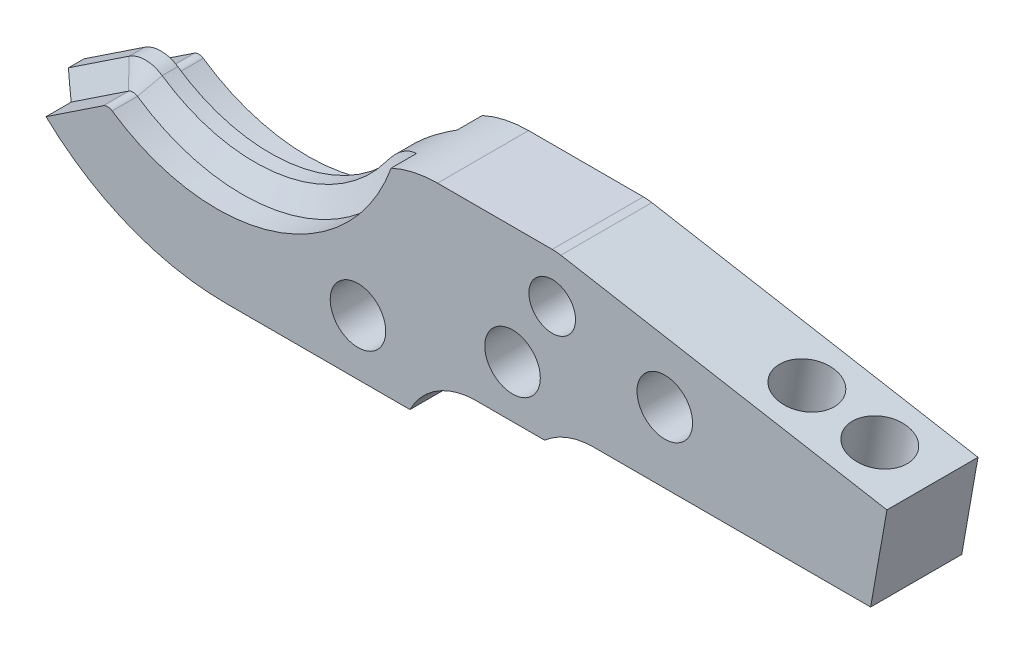
SolidWorks part; units mm, degrees
material "4140/42 H.R STEEL"
ref_plane "Front Plane" through (0, 0, 0) normal (0, 0, 1) x (1, 0, 0)
ref_plane "Top Plane" through (0, 0, 0) normal (0, 1, 0) x (1, 0, 0)
ref_plane "Right Plane" through (0, 0, 0) normal (1, 0, 0) x (0, 0, -1)
sketch "Sketch1" plane through (0, 0, 0) normal (0, 0, 1) x (1, 0, 0)
  line L0 (-18.5234, -21.0526) -> (-31.9565, -29.9967)
  line L1 (26.5581, -9) -> (139.7, -9)
  line L2 (139.7, -9) -> (139.7, -21.7)
  line L3 (139.7, -21.7) -> (152.4, -21.7)
  line L4 (152.4, -21.7) -> (152.4, -38)
  line L5 (33.101, -45) -> (1.5875, -45)
  line L6 (0, 0) -> (-18.5234, -21.0526) construction
  line L9 (152.4, -38) -> (44.45, -38)
  arc A0 (-18.5234, -21.0526) -> (26.5581, -9) centre (0, 0) ccw
  arc A1 (-31.9565, -29.9967) -> (1.5875, -45) centre (1.5875, 0) ccw
  circle A2 centre (-18.7477, -27.305) radius 5.08 construction
  arc A3 (44.45, -38) -> (33.101, -45) centre (44.45, -50.7) ccw
  dimension "D1" = 28.0416
  dimension "D7" = 45
  dimension "D2" = 10.16
  dimension "D12" = 25.4
  dimension "D3" = 1.5875
  dimension "D4" = 152.4
  dimension "D5" = 12.7
  dimension "D6" = 22.225
  dimension "D8" = 9
  dimension "D9" = 12.7
  dimension "D10" = 7
  dimension "D11" = 107.95
  dimension "D13" = 165
extrude "Extrude1" add sketch "Sketch1" along normal blind 15.621
ref_plane "Plane1" through (26.5581, -9, 15.621) normal (-0.321, -0.9471, 0) x (0.9471, -0.321, 0)
sketch "Sketch3" plane through (26.5581, -9, 15.621) normal (-0.321, -0.9471, 0) x (0.9471, -0.321, 0)
  line L0 (-25.4, 0) -> (3.7084, 0)
  line L1 (3.7084, 0) -> (3.7084, -4.336)
  line L2 (3.7084, -4.336) -> (0, -6.477)
  line L3 (0, -6.477) -> (0, -9.144)
  line L4 (0, -9.144) -> (3.7084, -11.285)
  line L5 (3.7084, -11.285) -> (3.7084, -15.621)
  line L6 (3.7084, -15.621) -> (-25.4, -15.621)
  line L7 (-25.4, -15.621) -> (-25.4, -7.8105)
  line L8 (-25.4, -7.8105) -> (-25.4, 0)
  line L9 (0, 0) -> (0, -15.621) construction
  line L10 (0, -7.8105) -> (-25.4, -7.8105) construction
  line L11 (107.1562, 0) -> (0, 0) construction
  line L12 (107.1562, -15.621) -> (0, -15.621) construction
  dimension "D2" = 2.667
  dimension "D1" = 60
  dimension "D4" = 30
  dimension "D6" = 3.7084
  dimension "D7" = 25.4
sketch "Sketch4" plane through (0, 0, 15.621) normal (0, 0, 1) x (1, 0, 0)
  line L0 (-18.5234, -21.0526) -> (-31.9565, -29.9967) construction
  line L1 (-21.5631, -23.0765) -> (-26.708, -26.5021)
  line L2 (-18.5234, -21.0526) -> (-31.9565, -29.9967) construction
  line L3 (-26.708, -26.5021) -> (-31.9565, -29.9967)
  arc A0 (-18.5234, -21.0526) -> (26.5581, -9) centre (0, 0) ccw construction
  arc A1 (-15.8723, -23.1171) -> (26.5581, -9) centre (0, 0) ccw
  circle A2 centre (-18.7477, -27.305) radius 5.08 construction
  arc A3 (-15.8723, -23.1171) -> (-21.5631, -23.0765) centre (-18.7477, -27.305) ccw
  circle A4 centre (-23.8926, -30.7306) radius 5.08 construction
  arc A5 (-31.9565, -29.9967) -> (1.5875, -45) centre (1.5875, 0) ccw construction
  dimension "D1" = 10.16
sweep "Cut-Sweep1" cut profiles "Sketch3" path "Sketch4"
sketch "Sketch5" plane through (0, 0, 15.621) normal (0, 0, 1) x (1, 0, 0)
  line L0 (38.333, 16.8038) -> (31.5322, 12.2756)
  line L1 (37.8261, -9) -> (139.7, -9)
  line L4 (1.5875, -45) -> (152.4, -45)
  line L5 (152.4, -45) -> (152.4, -21.7)
  line L6 (152.4, -21.7) -> (139.7, -21.7)
  line L7 (139.7, -21.7) -> (139.7, -9)
  line L8 (-31.9565, -29.9967) -> (-21.7058, -23.1715) construction
  line L9 (-83.2798, -105.3294) -> (187.5268, -105.3294)
  line L10 (-83.2798, -105.3294) -> (-83.2798, 60.7736)
  line L11 (-83.2798, 60.7736) -> (187.5268, 60.7736)
  line L12 (187.5268, -105.3294) -> (187.5268, 60.7736)
  arc A1 (-29.3263, -32.7007) -> (1.5875, -45) centre (1.5875, 0) ccw construction
  arc A2 (39.8354, 23.7087) -> (1.5875, -45) centre (1.5875, 0) ccw
  arc A3 (31.5322, 12.2756) -> (24.3124, 13.9728) centre (28.7168, 16.5041) cw
  arc A4 (22.5243, -16.7029) -> (37.8261, -9) centre (37.8261, -28.05) cw
  arc A5 (39.8354, 23.7087) -> (38.333, 16.8038) centre (35.5176, 21.0322) cw
  arc A8 (22.5243, -16.7029) -> (24.3124, 13.9728) centre (0, 0) cw
  spline S3 degree 3 poles (30.0703, -10.1902) (22.7075, -31.9169) (0.9404, -39.1591) (-17.9714, -26.1743) knots 0 0 0 0 1 1 1 1 weights 1 0.735689 0.735689 1 construction
  spline S4 degree 3 poles (30.0703, -10.1902) (22.7075, -31.9169) (0.9404, -39.1591) (-17.9714, -26.1743) knots 0 0 0 0 1 1 1 1 weights 1 0.735689 0.735689 1 construction
  dimension "D1" = 5.08
  dimension "D2" = 19.05
  dimension "D3" = 28.0416
extrude "Extrude2" cut sketch "Sketch5" against normal through all
sketch "Sketch6" plane through (0, 0, 0) normal (0, 0, -1) x (-1, 0, 0)
  circle A0 centre (-57.5, -17.4625) radius 4
  dimension "D1" = 8
  dimension "D2" = 57.5
  dimension "D3" = 17.4625
extrude "Extrude3" cut sketch "Sketch6" against normal through all
sketch "Sketch7" plane through (0, 0, 0) normal (0, 0, -1) x (-1, 0, 0)
  line L0 (-139.7, -9) -> (-37.8261, -9) construction
  line L1 (-58.9695, -9.1286) -> (-114.9066, -18.9918)
  line L2 (-1.5875, -45) -> (-33.101, -45) construction
  line L3 (-57.5, -9) -> (-152.4, -9)
  line L4 (-152.4, -9) -> (-152.4, -45)
  line L5 (-152.4, -45) -> (-110.3206, -45)
  line L6 (-114.9066, -18.9918) -> (-110.3206, -45)
  line L7 (-114.3, -17.4625) -> (-114.3, -85.3181) construction
  line L8 (-105.5306, -72.1653) -> (-122.6103, 24.6983) construction
  line L9 (-152.4, -38) -> (-152.4, -21.7) construction
  arc A0 (-57.5, -9) -> (-58.9695, -9.1286) centre (-57.5, -17.4625) ccw
  circle A3 centre (-57.5, -17.4625) radius 56.8 construction
  dimension "D1" = 10
  dimension "D3" = 114.3
  dimension "D4" = 10
extrude "Extrude4" cut sketch "Sketch7" against normal through all
sketch "Sketch8" plane through (0.9701, 1.0983, 0) normal (0.1736, 0.9848, 0) x (0.9848, -0.1736, 0)
  line L0 (62.8941, 0) -> (54.8941, 0) construction
  line L1 (62.8941, 0) -> (54.8941, 0) construction
  line L2 (58.8941, 0) -> (58.8941, -15.621) construction
  line L3 (58.8941, -7.8105) -> (106.5191, -7.8105) construction
  line L4 (58.8941, -15.621) -> (115.6941, -15.621) construction
  circle A0 centre (106.5191, -7.8105) radius 4.7625
  circle A1 centre (93.8191, -7.8105) radius 4.7625
  dimension "D1" = 9.525
  dimension "D2" = 47.625
  dimension "D3" = 12.7
extrude "Extrude5" [suppressed] cut sketch "Sketch8" against normal blind 16.8402
hole_wizard "3/8 (0.375) Diameter Hole1" positions "Sketch10" profile "Sketch9" hole size "3/8" standard "Peddi Ansi Inch"
sketch "Sketch10" plane through (0, 0, 0) normal (0, 0, -1) x (-1, 0, 0)
  line L0 (-1.5875, -45) -> (-33.101, -45) construction
  line L2 (-1.5875, -45) -> (-33.101, -45) construction
  point P0 (-24.1816, -35.475)
  point P1 (-50.6941, -29.125)
  point P3 (-76.8066, -22.775)
  dimension "D1" = 90.725
  dimension "D2" = 64.2125
  dimension "D3" = 38.1
  dimension "D4" = 9.525
  dimension "D5" = 22.225
  dimension "D6" = 15.875
sketch "Sketch9" plane through (24.1816, -35.475, 0) normal (1, 0, 0) x (0, 1, 0)
  line L0 (0, 0) -> (0, 27.1334)
  line L1 (0, 27.1334) -> (4.7625, 25.4)
  line L2 (4.7625, 25.4) -> (4.7625, 0)
  line L5 (4.7625, 0) -> (0, 0)
  line L10 (0, 27.1334) -> (-4.7625, 25.4) construction
  line L11 (0, -6.35) -> (0, 107.95) construction
  dimension "Hole Dia." = 9.525
  dimension "Hole Depth" = 25.4
  dimension "Drill Angle" = 140
hole_wizard "3/8 (0.375) Diameter Hole2" positions "Sketch12" profile "Sketch11" hole size "3/8" standard "Peddi Ansi Inch"
sketch "Sketch12" plane through (0.2171, 1.2311, 0) normal (0.1736, 0.9848, 0) x (-0.9848, 0.1736, 0)
  line L0 (-116.4588, 7.8105) -> (-107.2838, 7.8105) construction
  line L1 (-116.4588, 15.621) -> (-116.4588, 0) construction
  line L3 (-59.6588, 15.621) -> (-59.6588, 0) construction
  point P0 (-94.5838, 7.8105)
  point P1 (-107.2838, 7.8105)
  dimension "D1" = 12.7
  dimension "D2" = 47.625
sketch "Sketch11" plane through (93.3639, -15.1932, 7.8105) normal (0, 0, 1) x (-0.9848, 0.1736, 0)
  line L0 (0, 0) -> (0, 11.4974)
  line L1 (0, 11.4974) -> (4.7625, 9.764)
  line L2 (4.7625, 9.764) -> (4.7625, 0)
  line L5 (4.7625, 0) -> (0, 0)
  line L10 (0, 11.4974) -> (-4.7625, 9.764) construction
  line L11 (0, -6.35) -> (0, 107.95) construction
  dimension "Hole Dia." = 9.525
  dimension "Hole Depth" = 9.764
  dimension "Drill Angle" = 140
sketch "Sketch13" plane through (0, 0, 15.621) normal (0, 0, 1) x (1, 0, 0)
  line L2 (44.45, -38) -> (111.5549, -38) construction
  line L3 (64.6008, -34.825) -> (112.1148, -34.825)
  arc A1 (64.6008, -34.825) -> (56.2005, -38) centre (64.6008, -47.525) ccw
  dimension "D3" = 12.7
  dimension "D2" = 6.1037
  dimension "D1" = 3.175
  dimension "D4" = 55.3544
  dimension "D5" = 46.9542
extrude "Extrude7" cut sketch "Sketch13" against normal through all and the other way through all flip side to cut
other "Freeze***"
